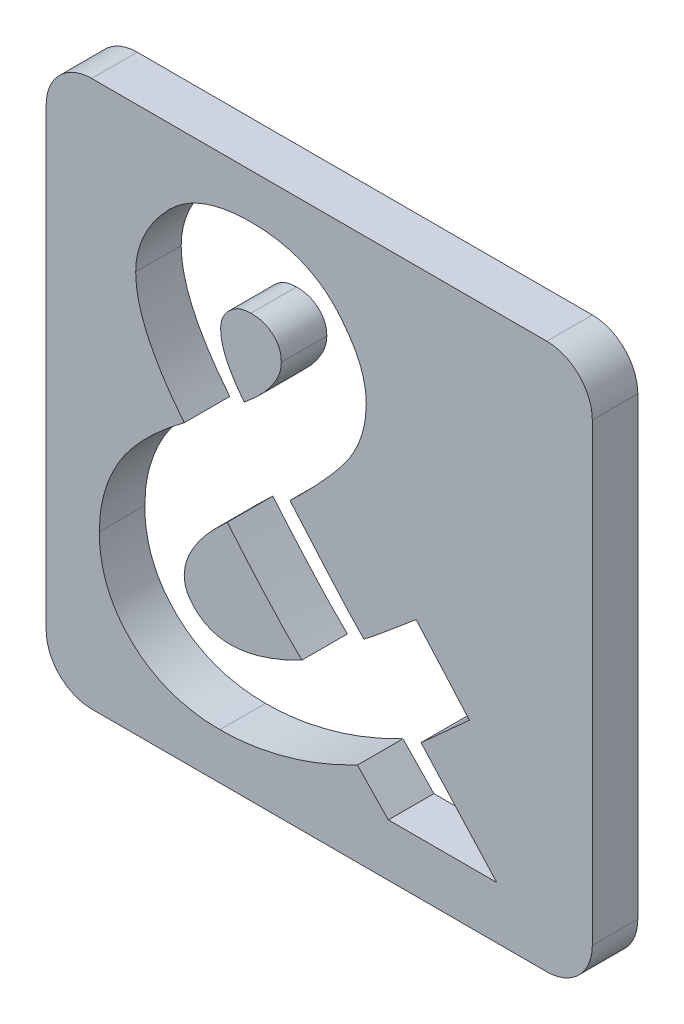
SolidWorks part; units mm, degrees
ref_plane "Front Plane" through (0, 0, 0) normal (0, 0, 1) x (1, 0, 0)
ref_plane "Top Plane" through (0, 0, 0) normal (0, 1, 0) x (1, 0, 0)
ref_plane "Right Plane" through (0, 0, 0) normal (1, 0, 0) x (0, 0, -1)
sketch "Sketch1" plane through (0, 0, 0) normal (0, 0, 1) x (1, 0, 0)
  line L1 (-50, 60) -> (50, 60)
  line L2 (-60, 50) -> (-60, -50)
  line L3 (-50, -60) -> (50, -60)
  line L4 (60, 50) -> (60, -50)
  line L5 (-60, 60) -> (60, -60) construction
  line L6 (-60, -60) -> (60, 60) construction
  arc A0 (-60, -50) -> (-50, -60) centre (-50, -50) ccw
  arc A1 (50, -60) -> (60, -50) centre (50, -50) ccw
  arc A2 (50, 60) -> (60, 50) centre (50, 50) cw
  arc A3 (-50, 60) -> (-60, 50) centre (-50, 50) ccw
  point P0 (0, 0)
  dimension "D3" = 10
  dimension "D1" = 120
  dimension "D2" = 120
extrude "Boss-Extrude1" add sketch "Sketch1" along normal blind 10 contours A3 L2 A0 L3 A1 L4 A2 L1
sketch "Sketch2" plane through (0, 0, 10) normal (0, 0, 1) x (1, 0, 0)
  line L0 (0, 0) -> (0, 40) construction
  line L1 (-50, 50) -> (50, 50) construction
  line L2 (-50, 50) -> (-50, -50) construction
  line L3 (-50, -50) -> (50, -50) construction
  line L4 (50, 50) -> (50, -50) construction
  line L5 (-50, 50) -> (50, -50) construction
  line L6 (-50, -50) -> (50, 50) construction
  line L7 (0, 40) -> (-40, 40) construction
  line L8 (-40, 40) -> (-40, 0) construction
  line L9 (-40, 0) -> (0, 0) construction
  line L11 (0, 20) -> (-20, 20) construction
  line L12 (-20, 40) -> (-20, 20) construction
  circle A0 centre (0, 40) radius 4 construction
  circle A1 centre (0, 20) radius 4 construction
  circle A2 centre (0, 0) radius 4 construction
  circle A3 centre (-20, 20) radius 4 construction
  circle A4 centre (-20, 40) radius 4 construction
  circle A5 centre (-40, 40) radius 4 construction
  circle A6 centre (0, 0) radius 4 construction
  circle A7 centre (20, 0) radius 4 construction
  circle A8 centre (40, 0) radius 4 construction
  circle A9 centre (40, 20) radius 4 construction
  circle A10 centre (40, 40) radius 4 construction
  circle A11 centre (20, 20) radius 4 construction
  circle A12 centre (0, 0) radius 4 construction
  circle A13 centre (0, -20) radius 4 construction
  circle A14 centre (0, -40) radius 4 construction
  circle A15 centre (20, -40) radius 4 construction
  circle A16 centre (40, -40) radius 4 construction
  circle A17 centre (20, -20) radius 4 construction
  circle A18 centre (0, 0) radius 4 construction
  circle A19 centre (-20, 0) radius 4 construction
  circle A20 centre (-40, 0) radius 4 construction
  circle A21 centre (-40, -20) radius 4 construction
  circle A22 centre (-40, -40) radius 4 construction
  circle A23 centre (-20, -20) radius 4 construction
  text T0 "&" font "Century Gothic" height 104
  point P0 (0, 0)
  point P55 (0, 0)
  dimension "D4" = 8
  dimension "D1" = 100
  dimension "D2" = 100
  dimension "D3" = 40
  dimension "D5" = 4
extrude "Cut-Extrude13" cut sketch "Sketch2" against normal blind 10
